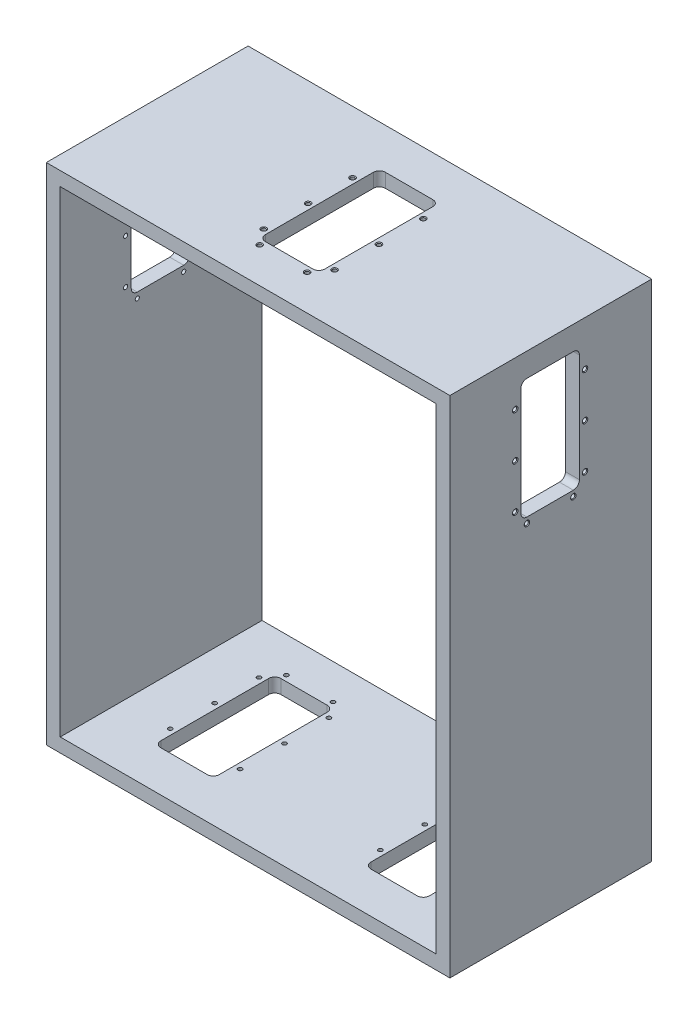
SolidWorks part; units mm, degrees
ref_plane "Plano frontal" through (0, 0, 0) normal (0, 0, 1) x (1, 0, 0)
ref_plane "Plano superior" through (0, 0, 0) normal (0, 1, 0) x (1, 0, 0)
ref_plane "Plano direito" through (0, 0, 0) normal (1, 0, 0) x (0, 0, -1)
sketch "Esboço1" plane through (0, 0, 0) normal (0, 0, 1) x (1, 0, 0)
  line L1 (100, 125) -> (-100, 125)
  line L2 (100, 125) -> (100, -125)
  line L3 (100, -125) -> (-100, -125)
  line L4 (-100, 125) -> (-100, -125)
  line L5 (100, 125) -> (-100, -125) construction
  line L6 (100, -125) -> (-100, 125) construction
  point P0 (0, 0)
  dimension "D1" = 200
  dimension "D2" = 250
extrude "Ressalto-extrusão2" add sketch "Esboço1" along normal blind 100
sketch "Esboço6" plane through (0, 0, 0) normal (0, 0, -1) x (-1, 0, 0)
  line L1 (93.1, 118.1) -> (-93.1, 118.1)
  line L2 (93.1, 118.1) -> (93.1, -118.1)
  line L3 (93.1, -118.1) -> (-93.1, -118.1)
  line L4 (-93.1, 118.1) -> (-93.1, -118.1)
  line L5 (93.1, 118.1) -> (-93.1, -118.1) construction
  line L6 (93.1, -118.1) -> (-93.1, 118.1) construction
  point P0 (0, 0)
  dimension "D1" = 236.2
  dimension "D2" = 186.2
extrude "Corte-extrusão3" cut sketch "Esboço6" against normal blind 100
sketch "Esboço7" plane through (100, 0, 0) normal (1, 0, 0) x (0, 0, -1)
  line L5 (-35.8184, 113.2723) -> (-64.8184, 113.2723)
  line L6 (-35.8184, 113.2723) -> (-35.8184, 53.7723)
  line L7 (-35.8184, 53.7723) -> (-64.8184, 53.7723)
  line L8 (-64.8184, 113.2723) -> (-64.8184, 53.7723)
  line L9 (-35.8184, 113.2723) -> (-64.8184, 53.7723) construction
  line L10 (-35.8184, 53.7723) -> (-64.8184, 113.2723) construction
  point P0 (-50.3184, 83.5223)
  dimension "D1" = 29
  dimension "D2" = 59.5
extrude "Corte-extrusão4" cut sketch "Esboço7" against normal blind 213
fillet "Filete1" radius 3 8 edges at (-96.55, 53.7723, 64.8184) (-96.55, 53.7723, 35.8184) (-96.55, 113.2723, 35.8184) (-96.55, 113.2723, 64.8184) (96.55, 53.7723, 35.8184) (96.55, 113.2723, 35.8184) (96.55, 53.7723, 64.8184) (96.55, 113.2723, 64.8184)
sketch "Esboço8" plane through (0, 0, 0) normal (1, 0, 0) x (0, 0, -1)
  line L0 (-64.8184, 110.2723) -> (-64.8184, 56.7723) construction
  line L2 (-61.8184, 53.7723) -> (-38.8184, 53.7723) construction
  circle A0 centre (-67.6184, 102.7723) radius 1.025
  circle A1 centre (-67.6184, 80.7723) radius 1.025
  circle A2 centre (-67.6184, 58.7723) radius 1.025
  circle A3 centre (-61.8184, 50.9723) radius 1.025
  circle A4 centre (-38.8184, 50.9723) radius 1.025
  circle A5 centre (-33.0184, 58.7723) radius 1.025
  circle A6 centre (-33.0184, 80.7723) radius 1.025
  circle A7 centre (-33.0184, 102.7723) radius 1.025
  point P13 (0, 0)
  dimension "D3" = 2.05
  dimension "D5" = 2.05
  dimension "D6" = 2.05
  dimension "D8" = 2.05
  dimension "D1" = 7.5
  dimension "D2" = 2.8
  dimension "D4" = 22
  dimension "D7" = 22
  dimension "D9" = 2.8
extrude "Corte-extrusão6" cut sketch "Esboço8" against normal through all both and the other way through all
chamfer "Chanfro2" distance 0.325 angle 45 8 edges at (100, 58.7723, 34.0434) (100, 50.9723, 39.8434) (100, 50.9723, 60.7934) (100, 58.7723, 66.5934) (100, 80.7723, 34.0434) (100, 102.7723, 34.0434) (100, 80.7723, 66.5934) (100, 102.7723, 66.5934)
chamfer "Chanfro3" distance 0.325 angle 45 8 edges at (-100, 58.7723, 66.5934) (-100, 50.9723, 60.7934) (-100, 50.9723, 39.8434) (-100, 58.7723, 34.0434) (-100, 80.7723, 34.0434) (-100, 80.7723, 66.5934) (-100, 102.7723, 66.5934) (-100, 102.7723, 34.0434)
sketch "Esboço10" plane through (0, 125, 0) normal (0, 1, 0) x (1, 0, 0)
  line L1 (14.7179, -20.1699) -> (-14.7821, -20.1699)
  line L2 (14.7179, -20.1699) -> (14.7179, -79.6699)
  line L3 (14.7179, -79.6699) -> (-14.7821, -79.6699)
  line L4 (-14.7821, -20.1699) -> (-14.7821, -79.6699)
  line L5 (14.7179, -20.1699) -> (-14.7821, -79.6699) construction
  line L6 (14.7179, -79.6699) -> (-14.7821, -20.1699) construction
  point P0 (-0.0321, -49.9199)
  dimension "D1" = 29.5
  dimension "D2" = 59.5
extrude "Corte-extrusão7" cut sketch "Esboço10" against normal blind 47
fillet "Filete2" radius 3 4 edges at (14.7179, 121.55, 79.6699) (-14.7821, 121.55, 79.6699) (14.7179, 121.55, 20.1699) (-14.7821, 121.55, 20.1699)
sketch "Esboço11" plane through (0, 125, 0) normal (0, 1, 0) x (1, 0, 0)
  line L0 (-14.7821, -23.1699) -> (-14.7821, -76.6699) construction
  line L1 (-11.7821, -79.6699) -> (11.7179, -79.6699) construction
  circle A0 centre (-17.5821, -30.6699) radius 1.025
  circle A1 centre (-17.5821, -52.6699) radius 1.025
  circle A2 centre (-17.5821, -74.6699) radius 1.025
  circle A3 centre (-11.7821, -82.4699) radius 1.025
  circle A4 centre (11.7179, -82.4699) radius 1.025
  circle A5 centre (17.5179, -74.6699) radius 1.025
  circle A6 centre (17.5179, -52.6699) radius 1.025
  circle A7 centre (17.5179, -30.6699) radius 1.025
  dimension "D3" = 2.05
  dimension "D6" = 2.05
  dimension "D7" = 2.05
  dimension "D8" = 2.05
  dimension "D1" = 7.5
  dimension "D2" = 2.8
  dimension "D4" = 22
  dimension "D5" = 22
  dimension "D9" = 2.8
extrude "Corte-extrusão8" cut sketch "Esboço11" against normal blind 9
chamfer "Chanfro4" distance 0.325 angle 45 8 edges at (18.5429, 125, 74.6699) (12.7429, 125, 82.4699) (-12.8071, 125, 82.4699) (-18.6071, 125, 74.6699) (18.5429, 125, 30.6699) (18.5429, 125, 52.6699) (-18.6071, 125, 52.6699) (-18.6071, 125, 30.6699)
sketch "Esboço12" plane through (0, -125, 0) normal (0, -1, 0) x (1, 0, 0)
  line L3 (37.5577, 20.2227) -> (66.5577, 20.2227)
  line L4 (-37.5577, 79.7227) -> (-66.5577, 79.7227)
  line L5 (-37.5577, 79.7227) -> (-37.5577, 20.2227)
  line L6 (-37.5577, 20.2227) -> (-66.5577, 20.2227)
  line L7 (-66.5577, 79.7227) -> (-66.5577, 20.2227)
  line L8 (-37.5577, 79.7227) -> (-66.5577, 20.2227) construction
  line L9 (-37.5577, 20.2227) -> (-66.5577, 79.7227) construction
  line L10 (66.5577, 79.7227) -> (66.5577, 20.2227)
  line L11 (37.5577, 79.7227) -> (66.5577, 79.7227)
  line L12 (37.5577, 79.7227) -> (37.5577, 20.2227)
  point P6 (-52.0577, 49.9727)
  dimension "D1" = 29
  dimension "D2" = 59.5
extrude "Corte-extrusão9" cut sketch "Esboço12" against normal blind 23
fillet "Filete3" radius 3 8 edges at (-66.5577, -121.55, 20.2227) (37.5577, -121.55, 20.2227) (66.5577, -121.55, 20.2227) (-37.5577, -121.55, 20.2227) (66.5577, -121.55, 79.7227) (-37.5577, -121.55, 79.7227) (37.5577, -121.55, 79.7227) (-66.5577, -121.55, 79.7227)
sketch "Esboço13" plane through (0, -125, 0) normal (0, -1, 0) x (1, 0, 0)
  line L4 (-63.5577, 20.2227) -> (-40.5577, 20.2227) construction
  line L5 (-66.5577, 76.7227) -> (-66.5577, 23.2227) construction
  circle A0 centre (-69.3577, 69.2227) radius 1.025
  arc A1 (-63.5577, 79.7227) -> (-66.5577, 76.7227) centre (-63.5577, 76.7227) ccw construction
  circle A2 centre (-69.3577, 47.2227) radius 1.025
  circle A3 centre (-69.3577, 25.2227) radius 1.025
  circle A4 centre (-63.6107, 17.4227) radius 1.025
  circle A5 centre (-40.5047, 17.4227) radius 1.025
  circle A6 centre (-34.7577, 25.2227) radius 1.025
  circle A7 centre (-34.7577, 47.2227) radius 1.025
  circle A8 centre (-34.7577, 69.2227) radius 1.025
  circle A9 centre (34.7577, 25.2227) radius 1.025
  circle A10 centre (40.5047, 17.4227) radius 1.025
  circle A11 centre (63.6107, 17.4227) radius 1.025
  circle A12 centre (69.3577, 25.2227) radius 1.025
  circle A13 centre (69.3577, 47.2227) radius 1.025
  circle A14 centre (34.7577, 47.2227) radius 1.025
  circle A15 centre (34.7577, 69.2227) radius 1.025
  circle A16 centre (69.3577, 69.2227) radius 1.025
  dimension "D2" = 2.05
  dimension "D4" = 2.05
  dimension "D7" = 2.05
  dimension "D9" = 2.05
  dimension "D1" = 7.5
  dimension "D3" = 2.8
  dimension "D5" = 22
  dimension "D6" = 22
  dimension "D8" = 2.8
extrude "Corte-extrusão10" cut sketch "Esboço13" against normal blind 23
chamfer "Chanfro5" distance 0.325 angle 45 16 edges at (68.3327, -125, 69.2227) (68.3327, -125, 47.2227) (68.3327, -125, 25.2227) (62.5857, -125, 17.4227) (41.5297, -125, 17.4227) (35.7827, -125, 25.2227) (35.7827, -125, 47.2227) (35.7827, -125, 69.2227) (-35.7827, -125, 69.2227) (-35.7827, -125, 47.2227) (-35.7827, -125, 25.2227) (-41.5297, -125, 17.4227) (-62.5857, -125, 17.4227) (-68.3327, -125, 25.2227) (-68.3327, -125, 47.2227) (-68.3327, -125, 69.2227)
